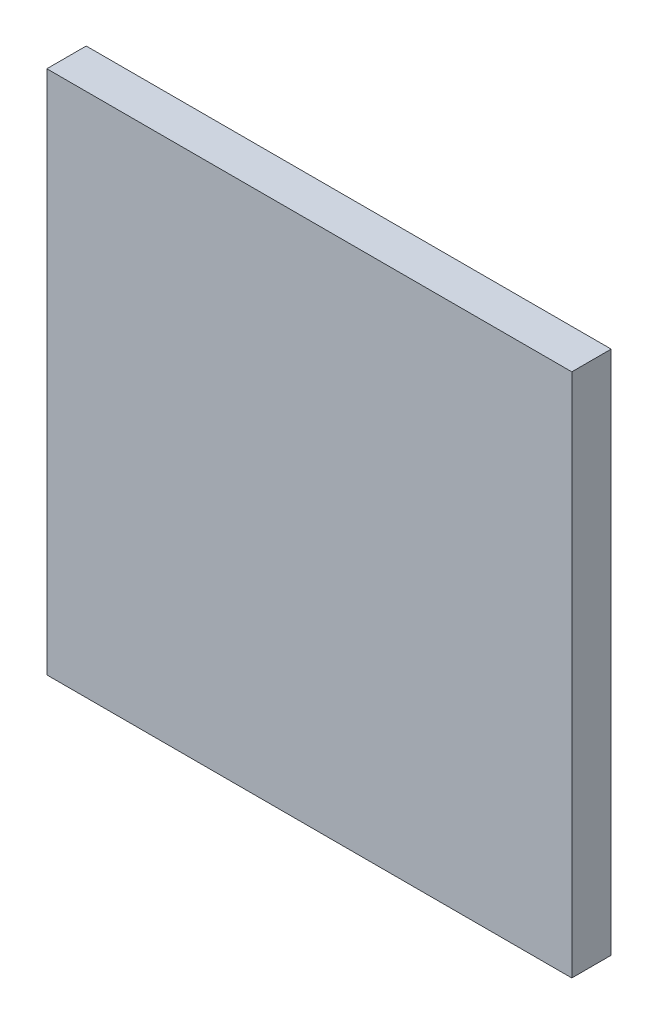
SolidWorks part; units mm, degrees
ref_plane "前视基准面" through (0, 0, 0) normal (0, 0, 1) x (1, 0, 0)
ref_plane "上视基准面" through (0, 0, 0) normal (0, 1, 0) x (1, 0, 0)
ref_plane "右视基准面" through (0, 0, 0) normal (1, 0, 0) x (0, 0, -1)
sketch "草图1" plane through (0, 0, 0) normal (0, 0, 1) x (1, 0, 0)
  line L0 (-0.2, -0.2) -> (0.2, -0.2)
  line L1 (0.2, -0.2) -> (0.2, 0.2)
  line L2 (0.2, 0.2) -> (-0.2, 0.2)
  line L3 (-0.2, 0.2) -> (-0.2, -0.2)
extrude "Component_Outline" add sketch "草图1" along normal blind 0.03 separate body
sketch3d "3D草图1"
  line L0 (0, 0, 0) -> (1, 0, 0)
  line L1 (0, 0, 0) -> (0, 1, 0)
  line L2 (0, 0, 0) -> (0, 0, 1)
  point P0 (0, 0, 0)
